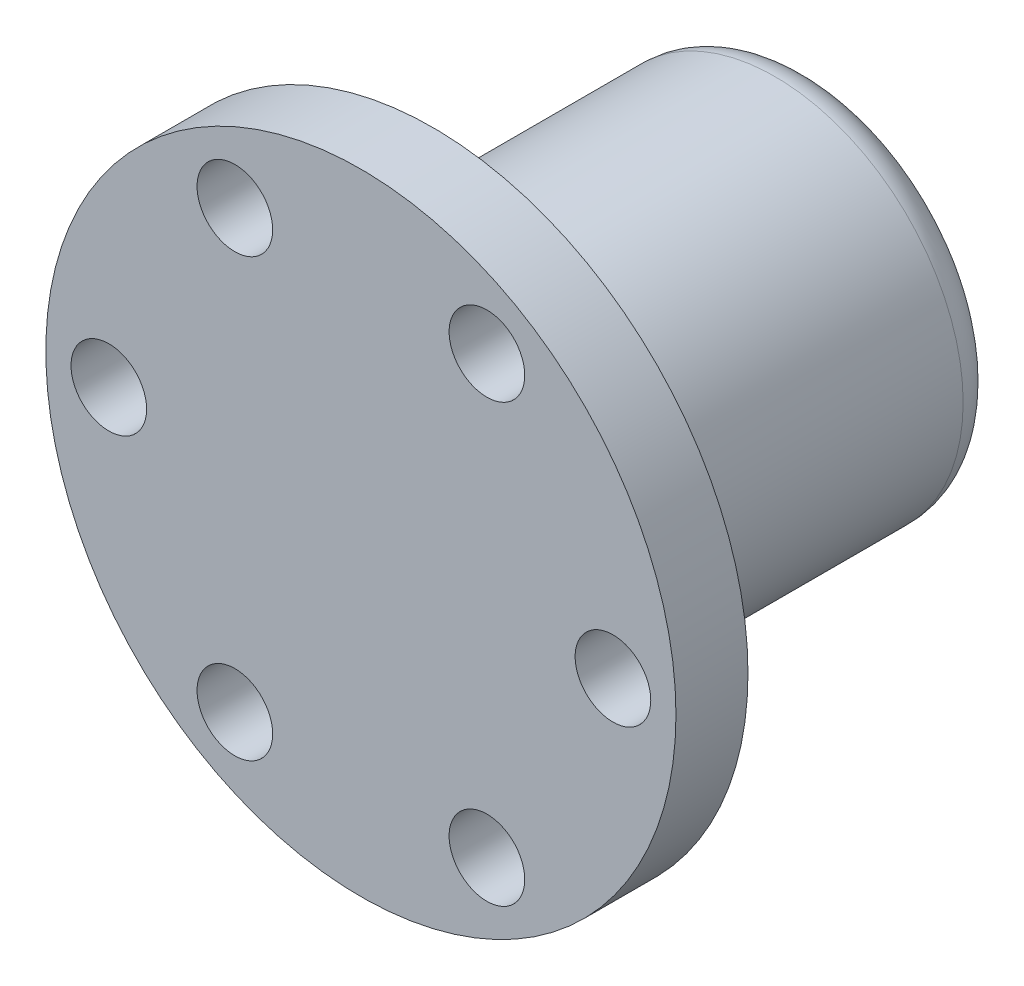
SolidWorks part; units mm, degrees
ref_plane "Front Plane" through (0, 0, 0) normal (0, 0, 1) x (1, 0, 0)
ref_plane "Top Plane" through (0, 0, 0) normal (0, 1, 0) x (1, 0, 0)
ref_plane "Right Plane" through (0, 0, 0) normal (1, 0, 0) x (0, 0, -1)
sketch "Sketch1" plane through (0, 0, 0) normal (0, 0, 1) x (1, 0, 0)
  circle A0 centre (0, 0) radius 10.45
  dimension "D1" = 20.9
extrude "Boss-Extrude1" add sketch "Sketch1" along normal blind 21
sketch "Sketch2" plane through (0, 0, 21) normal (0, 0, 1) x (1, 0, 0)
  circle A0 centre (0, 0) radius 17.5
  dimension "D1" = 35
extrude "Boss-Extrude2" add sketch "Sketch2" along normal blind 4
sketch "Sketch3" plane through (0, 0, 25) normal (0, 0, 1) x (1, 0, 0)
  line L0 (0, 0) -> (18.8194, 0) construction
  circle A0 centre (0, 0) radius 14 construction
  circle A1 centre (14, 0) radius 2.1
  circle A2 centre (7, -12.1244) radius 2.1
  circle A3 centre (-7, -12.1244) radius 2.1
  circle A4 centre (-14, 0) radius 2.1
  circle A5 centre (-7, 12.1244) radius 2.1
  circle A6 centre (7, 12.1244) radius 2.1
  point P18 (0, 0)
  dimension "D1" = 28
  dimension "D2" = 4.2
  dimension "D3" = 6
extrude "Cut-Extrude1" cut sketch "Sketch3" against normal through all
fillet "Fillet1" radius 2 1 edges at (10.45, 0, 0)
